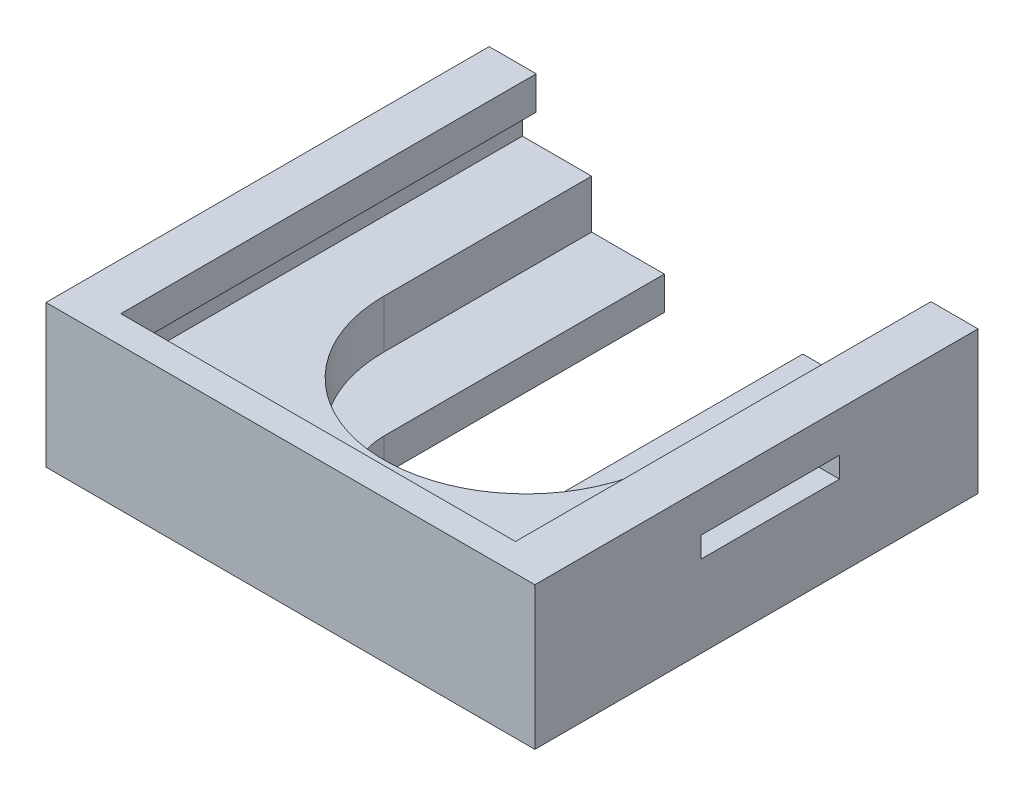
SolidWorks part; units mm, degrees
ref_plane "Alzado" through (0, 0, 0) normal (0, 0, 1) x (1, 0, 0)
ref_plane "Planta" through (0, 0, 0) normal (0, 1, 0) x (1, 0, 0)
ref_plane "Vista lateral" through (0, 0, 0) normal (1, 0, 0) x (0, 0, -1)
sketch "Croquis1" plane through (0, 0, 0) normal (0, 0, 1) x (1, 0, 0)
  line L0 (15.25, 0) -> (15.25, -3.5) construction
  line L1 (0, 0) -> (30.5, 0)
  line L2 (0, 0) -> (0, 2)
  line L3 (0, 2) -> (1, 2)
  line L4 (30.5, 0) -> (30.5, 2)
  line L5 (32.9, 4.4) -> (32.9, -5.9)
  line L6 (29.5, 4.4) -> (32.9, 4.4)
  line L7 (29.5, 2) -> (29.5, 4.4)
  line L8 (30.5, 2) -> (29.5, 2)
  line L9 (30.5, 0) -> (30.5, 2)
  line L10 (1, 2) -> (1, 4.4)
  line L11 (1, 4.4) -> (-2.4, 4.4)
  line L12 (-2.4, 4.4) -> (-2.4, -5.9)
  line L13 (-2.4, -5.9) -> (32.9, -5.9)
  point P15 (0, 0)
  dimension "D1" = 2
  dimension "D2" = 30.5
  dimension "D3" = 2.4
  dimension "D4" = 3.5
  dimension "D5" = 2.4
  dimension "D6" = 1
  dimension "D7" = 2.4
extrude "Saliente-Extruir1" add sketch "Croquis1" along normal blind 30
sketch "Croquis2" plane through (0, 0, 0) normal (0, 1, 0) x (1, 0, 0)
  line L0 (0, 0) -> (30.5, -30) construction
  line L1 (5, -15) -> (5, 0)
  line L2 (0, 0) -> (30.5, 0) construction
  line L3 (5, 0) -> (25.5, 0)
  line L4 (25.5, 0) -> (25.5, -15)
  arc A0 (5, -15) -> (25.5, -15) centre (15.25, -15) ccw
  point P9 (15.25, -15)
  dimension "D1" = 20.5
extrude "Cortar-Extruir1" cut sketch "Croquis2" against normal blind 3.5
sketch "Croquis3" plane through (0, -3.5, 0) normal (0, 1, 0) x (1, 0, 0)
  line L0 (10.25, -20.25) -> (10.25, 0)
  line L1 (25.5, 0) -> (5, 0) construction
  line L2 (10.25, 0) -> (20.25, 0)
  line L3 (20.25, 0) -> (20.25, -20.25)
  arc A0 (10.25, -20.25) -> (20.25, -20.25) centre (15.25, -20.25) ccw
  arc A3 (5, -15) -> (25.5, -15) centre (15.25, -15) ccw construction
  point P10 (15.25, -25.25)
  point P14 (15.25, -25.25)
  dimension "D1" = 10
extrude "Cortar-Extruir2" cut sketch "Croquis3" against normal through all
sketch "Croquis4" plane through (30.5, 0, 0) normal (-1, 0, 0) x (0, 0, 1)
  line L0 (30, 0) -> (0, 0) construction
  line L1 (10, 0) -> (20, 0)
  line L2 (10, 0) -> (10, 1.5)
  line L3 (10, 1.5) -> (20, 1.5)
  line L4 (20, 0) -> (20, 1.5)
  line L5 (0, 4.4) -> (0, -5.9) construction
  dimension "D1" = 1.5
  dimension "D2" = 10
  dimension "D3" = 10
extrude "Cortar-Extruir3" cut sketch "Croquis4" against normal blind 3.5
sketch "Croquis5" plane through (0, 0, 30) normal (0, 0, 1) x (1, 0, 0)
  line L1 (-2.4, -5.9) -> (32.9, -5.9)
  line L2 (-2.4, -5.9) -> (-2.4, 4.4)
  line L3 (-2.4, 4.4) -> (32.9, 4.4)
  line L4 (32.9, -5.9) -> (32.9, 4.4)
extrude "Saliente-Extruir2" add sketch "Croquis5" along normal blind 2
